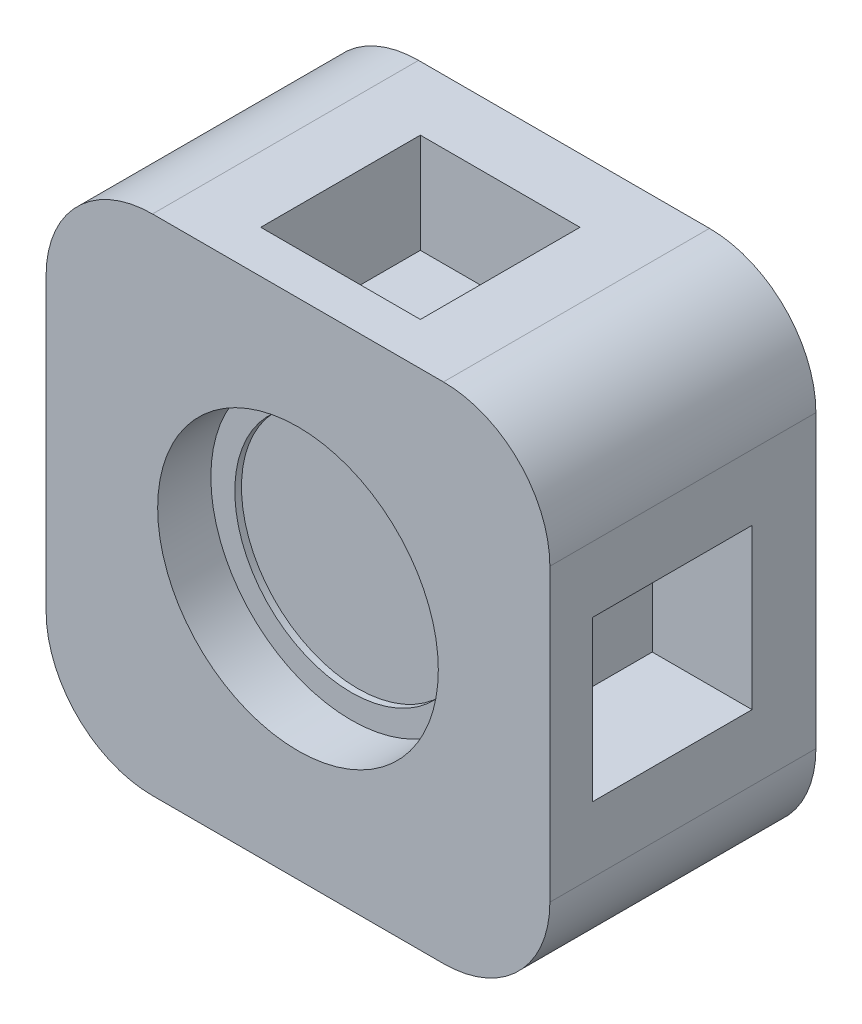
SolidWorks part; units mm, degrees
ref_plane "Ebene vorne" through (0, 0, 0) normal (0, 0, 1) x (1, 0, 0)
ref_plane "Ebene oben" through (0, 0, 0) normal (0, 1, 0) x (1, 0, 0)
ref_plane "Ebene rechts" through (0, 0, 0) normal (1, 0, 0) x (0, 0, -1)
sketch "Skizze1" plane through (0, 0, 0) normal (0, 1, 0) x (1, 0, 0)
  line L0 (0, 0) -> (12, 0) construction
  line L1 (12, 0) -> (18.9367, 6.9367) construction
  line L2 (18.9367, 6.9367) -> (18.9367, 18.9367) construction
  line L3 (18.9367, 12.9367) -> (-12.2794, 12.9367) construction
  line L4 (12, 25.8734) -> (18.9367, 18.9367) construction
  line L5 (0, 25.8734) -> (12, 25.8734) construction
  line L6 (6, 0) -> (6, 25.8734) construction
  line L7 (0, 0) -> (-6.9367, 6.9367) construction
  line L8 (-6.9367, 6.9367) -> (-6.9367, 18.9367) construction
  line L9 (0, 25.8734) -> (-6.9367, 18.9367) construction
  line L10 (24.9367, 31.8734) -> (24.9367, -6)
  line L11 (24.9367, -6) -> (-12.9367, -6)
  line L12 (-12.9367, 31.8734) -> (-12.9367, -6)
  line L13 (24.9367, 31.8734) -> (-12.9367, 31.8734)
  point P18 (6, -6)
  point P19 (24.9367, 12.9367)
  point P20 (-12.9367, 12.9367)
  dimension "D1" = 12
  dimension "D2" = 135
  dimension "D3" = 9.81
  dimension "D4" = 12
  dimension "D5" = 6
  dimension "D6" = 6
extrude "Aufsatz-Linear austragen1" add sketch "Skizze1" along normal blind 20
sketch "Skizze2" plane through (0, 0, 0) normal (0, -1, 0) x (1, 0, 0)
  line L0 (6, 6) -> (6, -31.8734) construction
  line L3 (-12.9367, -12.9367) -> (24.9367, -12.9367) construction
  line L5 (24.9367, -31.8734) -> (-12.9367, -31.8734) construction
  line L6 (24.9367, 6) -> (24.9367, -31.8734) construction
  circle A0 centre (6, -12.9367) radius 10.55
  point P11 (6, -12.9367)
  dimension "D1" = 21.1
extrude "Schnitt-Linear austragen1" cut sketch "Skizze2" against normal blind 4
sketch "Skizze3" plane through (0, 0, 6) normal (0, 0, 1) x (1, 0, 0)
  line L0 (6, 0) -> (6, 20) construction
  line L3 (0, 3.2) -> (12, 3.2)
  line L4 (12, 3.2) -> (12, 15.2)
  line L5 (12, 15.2) -> (0, 15.2)
  line L6 (0, 3.2) -> (0, 15.2)
  line L7 (-12.9367, 0) -> (24.9367, 0) construction
  line L8 (-12.9367, 20) -> (24.9367, 20) construction
  point P11 (6, 15.2)
  point P12 (6, 3.2)
  dimension "D1" = 3.2
  dimension "D2" = 12
  dimension "D3" = 12
extrude "Schnitt-Linear austragen3" cut sketch "Skizze3" against normal blind 7.5 contours L5 L6 L3 L4
fillet "Verrundung1" radius 8 4 edges at (-12.9367, 10, -31.8734) (24.9367, 10, -31.8734) (24.9367, 10, 6) (-12.9367, 10, 6)
pattern_circular "Kreismuster1" count 4 over 360 about axis through (6, 0, -12.9367) along (0, 1, 0) of "Schnitt-Linear austragen3"
sketch "Skizze4" plane through (0, 4, 0) normal (0, -1, 0) x (1, 0, 0)
  circle A0 centre (6, -12.9367) radius 8.75
  circle A1 centre (6, -12.9367) radius 10.55 construction
  dimension "D1" = 1.8
extrude "Schnitt-Linear austragen4" cut sketch "Skizze4" against normal blind 0.5
move or copy body "Körper-Verschieben/Kopieren1" bodies to move or copy 106 copy no rotation origin (0, 10, -12.9367) rotation axis (-1, 0, 0) rotation angle 90
